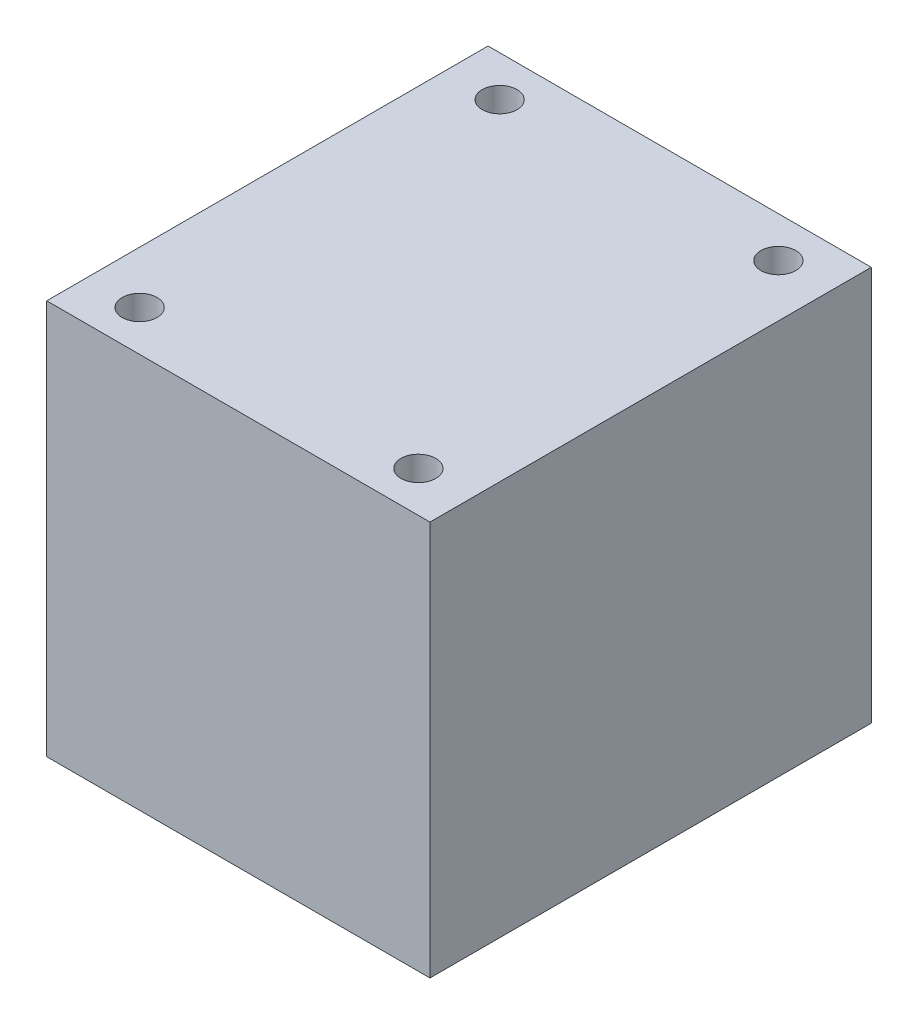
SolidWorks part; units mm, degrees
ref_plane "Front Plane" through (0, 0, 0) normal (0, 0, 1) x (1, 0, 0)
ref_plane "Top Plane" through (0, 0, 0) normal (0, 1, 0) x (1, 0, 0)
ref_plane "Right Plane" through (0, 0, 0) normal (1, 0, 0) x (0, 0, -1)
sketch "Sketch1" plane through (0, 0, 0) normal (0, 1, 0) x (1, 0, 0)
  line L1 (0, 0) -> (33, 0)
  line L2 (0, 0) -> (0, -38)
  line L3 (0, -38) -> (33, -38)
  line L4 (33, 0) -> (33, -38)
  circle A0 centre (28.5, -3.5) radius 1.5
  circle A1 centre (28.5, -34.5) radius 1.5
  circle A2 centre (4.5, -34.5) radius 1.5
  circle A3 centre (4.5, -3.5) radius 1.5
  dimension "D3" = 31
  dimension "D4" = 3.5
  dimension "D5" = 31
  dimension "D6" = 3.5
  dimension "D7" = 24
  dimension "D8" = 24
  dimension "D9" = 4.5
  dimension "D10" = 3
  dimension "D11" = 3
  dimension "D12" = 4.5
  dimension "D13" = 3
  dimension "D14" = 3
  dimension "D1" = 38
  dimension "D2" = 33
extrude "Boss-Extrude1" add sketch "Sketch1" along normal blind 34
